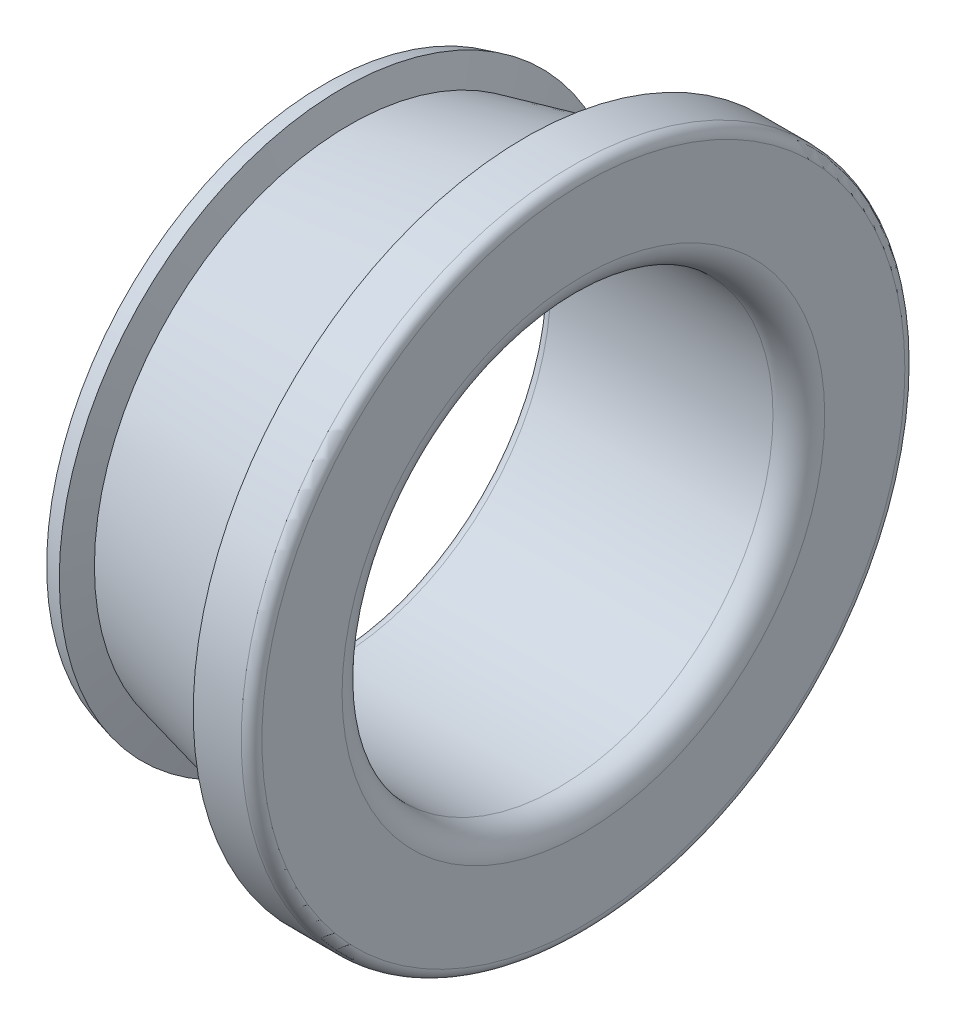
SolidWorks part; units mm, degrees
ref_plane "Plan1" through (0, 0, 0) normal (0, 0, 1) x (1, 0, 0)
ref_plane "Plan2" through (0, 0, 0) normal (0, 1, 0) x (1, 0, 0)
ref_plane "Plan3" through (0, 0, 0) normal (1, 0, 0) x (0, 0, -1)
sketch "Esquisse1" plane through (0, 0, 0) normal (0, 0, 1) x (1, 0, 0)
  line L0 (0, 0) -> (-29.1339, 0) construction
  line L1 (0, 14) -> (0, 18.65)
  line L2 (-1.5, 12.5) -> (-14.4, 12.5)
  line L3 (-15, 13.1) -> (-15, 16.1379)
  line L4 (-15, 16.1379) -> (-14, 16.4059)
  line L5 (-3.3856, 19.25) -> (-2.868, 17.3181)
  line L6 (-14, 16.4059) -> (-13.5693, 14.7983)
  line L7 (-2.868, 17.3181) -> (-13.5693, 14.7983)
  line L8 (-3.3856, 19.25) -> (-0.6, 19.25)
  arc A0 (0, 14) -> (-1.5, 12.5) centre (-1.5, 14) cw
  arc A1 (-14.4, 12.5) -> (-15, 13.1) centre (-14.4, 13.1) cw
  arc A2 (0, 18.65) -> (-0.6, 19.25) centre (-0.6, 18.65) ccw
  point P9 (0, 12.5)
  point P12 (-15, 12.5)
  point P17 (0, 19.25)
  dimension "D5" = 1.5
  dimension "D10" = 0.6
  dimension "D11" = 0.6
  dimension "D1" = 15
  dimension "D2" = 12.5
  dimension "D3" = 19.25
  dimension "D4" = 15
  dimension "D6" = 13.25
  dimension "D7" = 2
  dimension "D8" = 3.3856
  dimension "D9" = 1
revolve "Base-Révolution" add sketch "Esquisse1" angle 360 about L0
